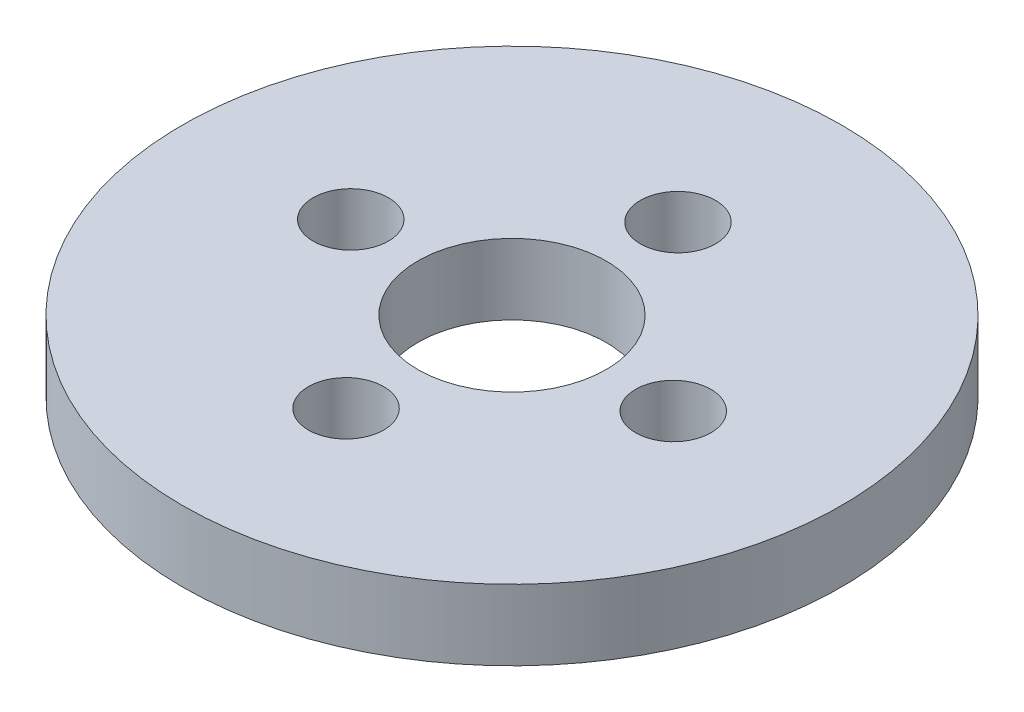
SolidWorks part; units mm, degrees
ref_plane "前视基准面" through (0, 0, 0) normal (0, 0, 1) x (1, 0, 0)
ref_plane "上视基准面" through (0, 0, 0) normal (0, 1, 0) x (1, 0, 0)
ref_plane "右视基准面" through (0, 0, 0) normal (1, 0, 0) x (0, 0, -1)
sketch "草图1" plane through (0, 0, 0) normal (0, 1, 0) x (1, 0, 0)
  line L1 (-4.5499, 1.3067) -> (-6.8999, 2.6635) construction
  line L2 (-1.2567, -4.7) -> (-2.6135, -7.05) construction
  line L3 (-2.6135, -7.05) -> (-1.2567, -9.4) construction
  line L4 (-1.2567, -9.4) -> (1.4568, -9.4) construction
  line L5 (1.4568, -9.4) -> (2.8136, -7.05) construction
  line L6 (2.8136, -7.05) -> (1.4568, -4.7) construction
  line L7 (1.4568, -4.7) -> (-1.2567, -4.7) construction
  line L8 (-6.8999, 2.6635) -> (-9.2499, 1.3067) construction
  line L9 (-9.2499, 1.3067) -> (-9.2499, -1.4068) construction
  line L10 (-9.2499, -1.4068) -> (-6.8999, -2.7636) construction
  line L11 (-6.8999, -2.7636) -> (-4.5499, -1.4068) construction
  line L12 (-4.5499, -1.4068) -> (-4.5499, 1.3067) construction
  line L14 (1.4568, 4.6) -> (2.8136, 6.95) construction
  line L15 (2.8136, 6.95) -> (1.4568, 9.3) construction
  line L16 (1.4568, 9.3) -> (-1.2567, 9.3) construction
  line L17 (-1.2567, 9.3) -> (-2.6135, 6.95) construction
  line L18 (-2.6135, 6.95) -> (-1.2567, 4.6) construction
  line L19 (-1.2567, 4.6) -> (1.4568, 4.6) construction
  line L20 (0, 14) -> (0, -14) construction
  line L21 (4.7501, -1.4068) -> (7.1001, -2.7636) construction
  line L22 (7.1001, -2.7636) -> (9.4501, -1.4068) construction
  line L23 (9.4501, -1.4068) -> (9.4501, 1.3067) construction
  line L24 (9.4501, 1.3067) -> (7.1001, 2.6635) construction
  line L25 (7.1001, 2.6635) -> (4.7501, 1.3067) construction
  line L26 (4.7501, 1.3067) -> (4.7501, -1.4068) construction
  line L27 (14.1001, 0) -> (-13.8999, 0) construction
  circle A0 centre (0, 0) radius 4
  circle A1 centre (-6.8999, -0.05) radius 2.35 construction
  circle A2 centre (0.1001, -7.05) radius 2.35 construction
  circle A3 centre (0.1001, 6.95) radius 2.35 construction
  circle A4 centre (7.1001, -0.05) radius 2.35 construction
  circle A5 centre (0, 0) radius 14
  circle A6 centre (0.1001, 6.95) radius 1.6
  circle A7 centre (6.95, -0.1001) radius 1.6
  circle A8 centre (-0.1001, -6.95) radius 1.6
  circle A9 centre (-6.95, 0.1001) radius 1.6
  point P13 (0, 0)
  point P36 (0, 0)
  point P38 (0, 0)
  point P51 (0, 0)
  dimension "D1" = 8
  dimension "D2" = 4.7
  dimension "D3" = 28
  dimension "D4" = 3.2
  dimension "D5" = 4
extrude "凸台-拉伸1" add sketch "草图1" along normal blind 3
